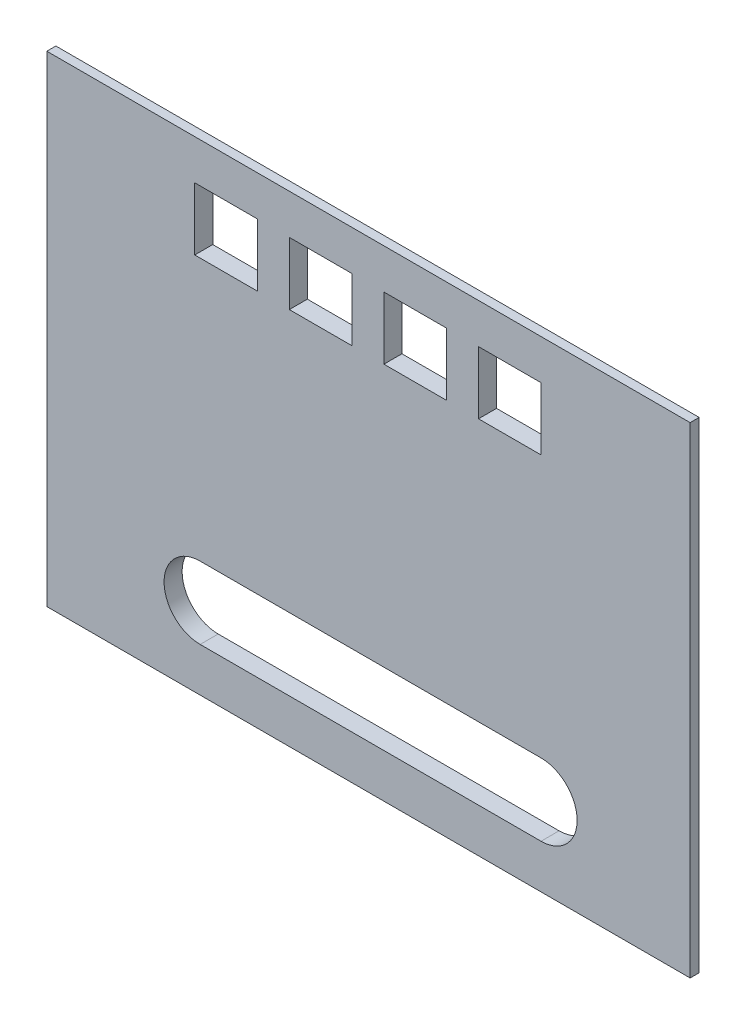
SolidWorks part; units mm, degrees
ref_plane "Спереди" through (0, 0, 0) normal (0, 0, 1) x (1, 0, 0)
ref_plane "Сверху" through (0, 0, 0) normal (0, 1, 0) x (1, 0, 0)
ref_plane "Справа" through (0, 0, 0) normal (1, 0, 0) x (0, 0, -1)
other "Configuration Table"
sketch "Эскиз1" plane through (0, 0, 0) normal (0, 0, 1) x (1, 0, 0)
  line L1 (3, 3) -> (104, 3)
  line L2 (3, 3) -> (3, 77)
  line L3 (3, 77) -> (104, 77)
  line L4 (104, 3) -> (104, 77)
extrude "Бобышка-Вытянуть1" add sketch "Эскиз1" along normal blind 3
sketch "Эскиз2" plane through (0, 0, 0) normal (0, 0, 1) x (1, 0, 0)
  line L1 (0, 0) -> (107, 0)
  line L2 (0, 0) -> (0, 80)
  line L3 (0, 80) -> (107, 80)
  line L4 (107, 0) -> (107, 80)
extrude "Бобышка-Вытянуть2" add sketch "Эскиз2" along normal blind 1.5 from offset 1.5
sketch "Эскиз3" plane through (0, 0, 3) normal (0, 0, 1) x (1, 0, 0)
  line L0 (25.5, 13.3) -> (82.2, 13.3) construction
  line L1 (24.6, 62.95) -> (35, 62.95)
  line L2 (24.6, 62.95) -> (24.6, 73.35)
  line L3 (24.6, 73.35) -> (35, 73.35)
  line L4 (35, 62.95) -> (35, 73.35)
  line L5 (40.333, 62.95) -> (50.733, 62.95)
  line L6 (40.333, 62.95) -> (40.333, 73.35)
  line L7 (40.333, 73.35) -> (50.733, 73.35)
  line L8 (50.733, 62.95) -> (50.733, 73.35)
  line L9 (56.067, 62.95) -> (66.467, 62.95)
  line L10 (56.067, 62.95) -> (56.067, 73.35)
  line L11 (56.067, 73.35) -> (66.467, 73.35)
  line L12 (66.467, 62.95) -> (66.467, 73.35)
  line L13 (71.8, 62.95) -> (82.2, 62.95)
  line L14 (71.8, 62.95) -> (71.8, 73.35)
  line L15 (71.8, 73.35) -> (82.2, 73.35)
  line L16 (82.2, 62.95) -> (82.2, 73.35)
  line L17 (25.5, 19.3) -> (82.2, 19.3)
  line L18 (25.5, 7.3) -> (82.2, 7.3)
  arc A0 (25.5, 19.3) -> (25.5, 7.3) centre (25.5, 13.3) ccw
  arc A1 (82.2, 7.3) -> (82.2, 19.3) centre (82.2, 13.3) ccw
  point P18 (53.85, 13.3)
extrude "Вырез-Вытянуть1" cut sketch "Эскиз3" against normal blind 5
